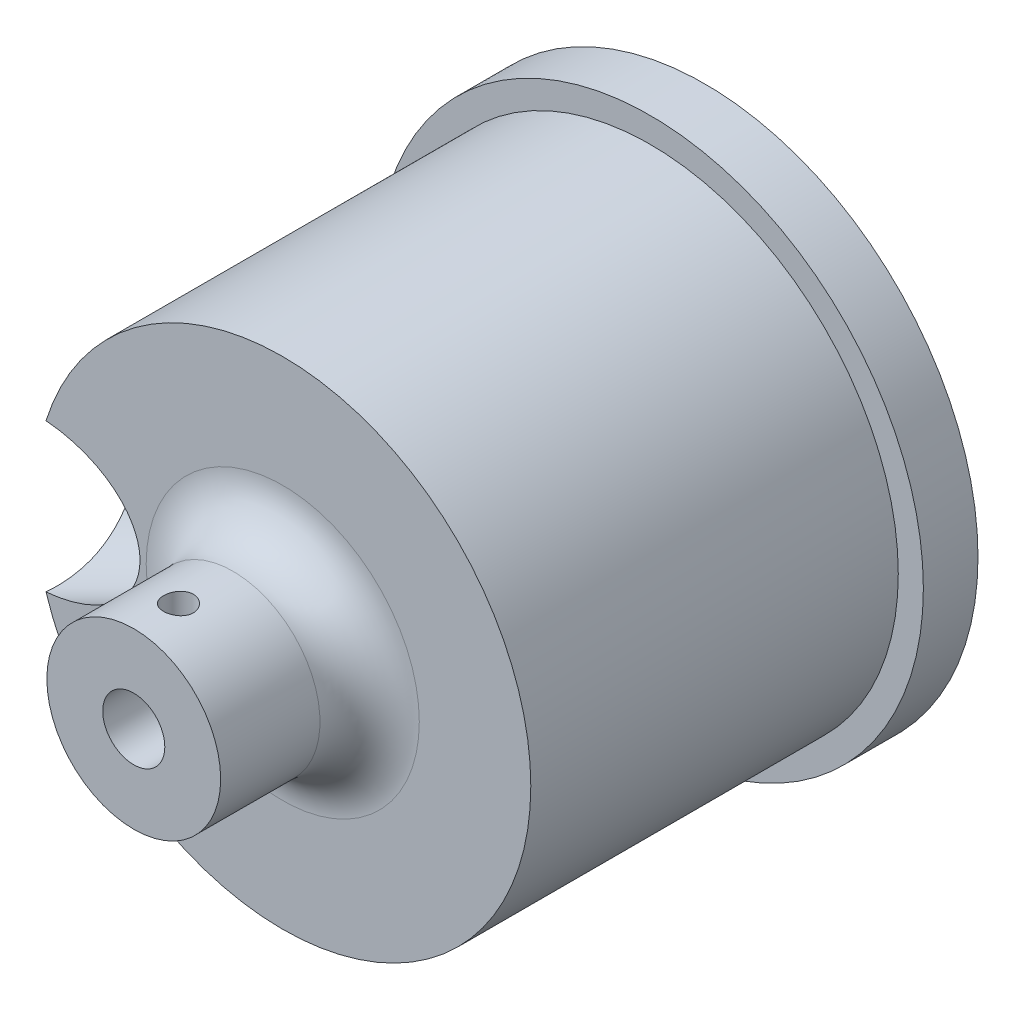
SolidWorks part; units mm, degrees
ref_plane "Ön Düzlem" through (0, 0, 0) normal (0, 0, 1) x (1, 0, 0)
ref_plane "Üst Düzlem" through (0, 0, 0) normal (0, 1, 0) x (1, 0, 0)
ref_plane "Sağ Düzlem" through (0, 0, 0) normal (1, 0, 0) x (0, 0, -1)
sketch "Çizim1" plane through (0, 0, 0) normal (0, 1, 0) x (1, 0, 0)
  line L0 (-27.5, 25) -> (-27.5, 12)
  line L1 (-27.5, 12) -> (-24.975, 12)
  line L2 (-24.975, 12) -> (-24.975, -25)
  line L3 (-24.975, -25) -> (0, -25)
  line L4 (0, -25) -> (0, 25) construction
  line L5 (0, 25) -> (-27.5, 25)
  line L6 (0, -25) -> (0, 25)
  dimension "D1" = 27.5
  dimension "D2" = 13
  dimension "D3" = 24.975
  dimension "D4" = 50
revolve "Döndür1" add sketch "Çizim1" angle 360 about L4
sketch "Çizim3" plane through (0, 0, -25) normal (0, 0, -1) x (-1, 0, 0)
  line L0 (0, 0) -> (15, 0) construction
  line L1 (15, 0) -> (7.5, 12.9904)
  line L2 (7.5, 12.9904) -> (-7.5, 12.9904)
  line L3 (-7.5, 12.9904) -> (-15, 0)
  line L4 (-15, 0) -> (-7.5, -12.9904)
  line L5 (-7.5, -12.9904) -> (7.5, -12.9904)
  line L6 (7.5, -12.9904) -> (15, 0)
  circle A1 centre (0, 0) radius 12.9904 construction
  dimension "D2" = 15
extrude "Kes-Ekstrüzyon1" cut sketch "Çizim3" against normal blind 7.5 flip side to cut
sketch "Çizim4" plane through (0, 0, 25) normal (0, 0, 1) x (1, 0, 0)
  circle A0 centre (0, 0) radius 8.75
  dimension "D1" = 17.5
extrude "Yükseklik-Ekstrüzyon1" add sketch "Çizim4" along normal blind 20
fillet "Radyus1" radius 5 1 edges at (8.75, 0, 25)
sketch "Çizim5" plane through (0, 0, 45) normal (0, 0, 1) x (1, 0, 0)
  line L0 (-2.2913, 2.125) -> (2.2913, 2.125)
  arc A0 (-2.2913, 2.125) -> (2.2913, 2.125) centre (0, 0) ccw
  dimension "D1" = 6.25
  dimension "D2" = 2.125
extrude "Kes-Ekstrüzyon2" cut sketch "Çizim5" against normal blind 20 contours L0 A0
sketch "Çizim6" plane through (0, 0, 0) normal (0, 1, 0) x (1, 0, 0)
  line L0 (0, 0) -> (0, -35.5) construction
  circle A0 centre (0, -35.5) radius 1.5
  dimension "D2" = 3
  dimension "D1" = 35.5
extrude "Kes-Ekstrüzyon3" cut sketch "Çizim6" along normal through all
sketch "Çizim7" plane through (0, 0, 45) normal (0, 0, 1) x (1, 0, 0)
  circle A0 centre (0, 0) radius 3.125
extrude "Kes-Ekstrüzyon4" cut sketch "Çizim7" against normal blind 11
sketch "Çizim8" plane through (0, 0, 45) normal (0, 0, 1) x (1, 0, 0)
  circle A1 centre (0, 0) radius 8.75
  circle A2 centre (0, 0) radius 8.75
  dimension "D1" = 0
extrude "Kes-Ekstrüzyon5" cut sketch "Çizim8" against normal blind 5
sketch "Çizim9" plane through (0, 0, -25) normal (0, 0, -1) x (-1, 0, 0)
  line L6 (7.5, -12.9904) -> (15, 0)
  line L7 (7.5, -12.9904) -> (15, 0)
  line L8 (15, 0) -> (7.5, 12.9904)
  line L9 (15, 0) -> (7.5, 12.9904)
  line L10 (7.5, 12.9904) -> (-7.5, 12.9904)
  line L11 (7.5, 12.9904) -> (-7.5, 12.9904)
  line L12 (-7.5, 12.9904) -> (-15, 0)
  line L13 (-7.5, 12.9904) -> (-15, 0)
  line L14 (-15, 0) -> (-7.5, -12.9904)
  line L15 (-15, 0) -> (-7.5, -12.9904)
  line L16 (-7.5, -12.9904) -> (7.5, -12.9904)
  line L17 (-7.5, -12.9904) -> (7.5, -12.9904)
  dimension "D1" = 0
extrude "Kes-Ekstrüzyon6" cut sketch "Çizim9" against normal blind 2.5
sketch "Çizim10" plane through (0, 0, 0) normal (0, 1, 0) x (1, 0, 0)
  line L0 (0, 22.5) -> (0, 0)
  line L1 (-7.5, 22.5) -> (7.5, 22.5) construction
  line L2 (0, 0) -> (-24.975, -25)
sketch "Çizim11" plane through (0, 0, -22.5) normal (0, 0, -1) x (-1, 0, 0)
  circle A0 centre (0, 0) radius 7.5
  dimension "D1" = 15
sweep "Kes-Süpür1" cut profiles "Çizim11" path "Çizim10"
